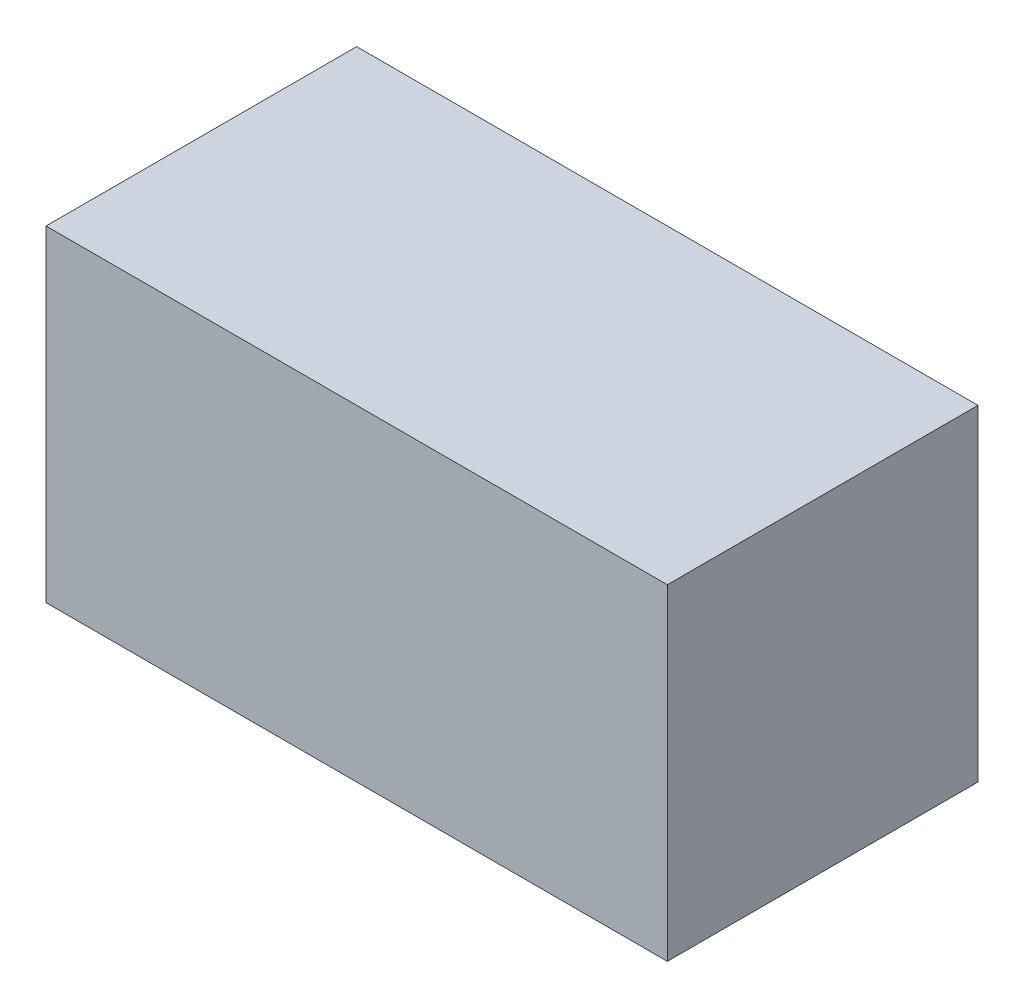
SolidWorks part; units mm, degrees
material "ABS"
ref_plane "Alzado" through (0, 0, 0) normal (0, 0, 1) x (1, 0, 0)
ref_plane "Planta" through (0, 0, 0) normal (0, 1, 0) x (1, 0, 0)
ref_plane "Vista lateral" through (0, 0, 0) normal (1, 0, 0) x (0, 0, -1)
sketch "Croquis base" plane through (0, 0, 0) normal (0, 1, 0) x (1, 0, 0)
  line L1 (-20, -10) -> (20, -10)
  line L2 (-20, -10) -> (-20, 10)
  line L3 (-20, 10) -> (20, 10)
  line L4 (20, -10) -> (20, 10)
  line L5 (-20, -10) -> (20, 10) construction
  line L6 (-20, 10) -> (20, -10) construction
  point P0 (0, 0)
  dimension "D1" = 40
  dimension "D2" = 20
extrude "Saliente-Extruir1" add sketch "Croquis base" along normal blind 21
sketch "Croquis socket" plane through (-20, 0, 0) normal (-1, 0, 0) x (0, 0, 1)
  line L0 (0, 21) -> (0, 0) construction
  line L1 (-10, 21) -> (10, 21) construction
  line L2 (-10, 0) -> (10, 0) construction
  line L3 (-3.45, 0) -> (3.45, 0)
  line L4 (-3.45, 0) -> (-3.45, 4)
  line L5 (-3.45, 4) -> (3.45, 4)
  line L6 (3.45, 0) -> (3.45, 4)
  dimension "D1" = 4
  dimension "D2" = 6.9
  dimension "D3" = 3.45
extrude "Saliente-Extruir2" add sketch "Croquis socket" along normal blind 1.5
sketch "Croquis socket 2" plane through (-21.5, 0, 0) normal (-1, 0, 0) x (0, 0, 1)
  line L0 (-3.45, 2) -> (3.45, 2) construction
  line L1 (-3.45, 4) -> (-3.45, 0) construction
  line L2 (3.45, 0) -> (3.45, 4) construction
  line L3 (0, 4) -> (0, 0) construction
  line L4 (3.45, 4) -> (-3.45, 4) construction
  line L6 (-2.95, 3.5) -> (2.95, 3.5)
  line L7 (-2.95, 3.5) -> (-2.95, 0.5)
  line L8 (-2.95, 0.5) -> (2.95, 0.5)
  line L9 (2.95, 3.5) -> (2.95, 0.5)
  line L10 (-2.95, 3.5) -> (2.95, 0.5) construction
  line L11 (-2.95, 0.5) -> (2.95, 3.5) construction
  point P11 (0, 2)
  dimension "D1" = 3
  dimension "D2" = 5.9
extrude "Saliente-Extruir4" add sketch "Croquis socket 2" along normal blind 3.7 draft 5 separate body
